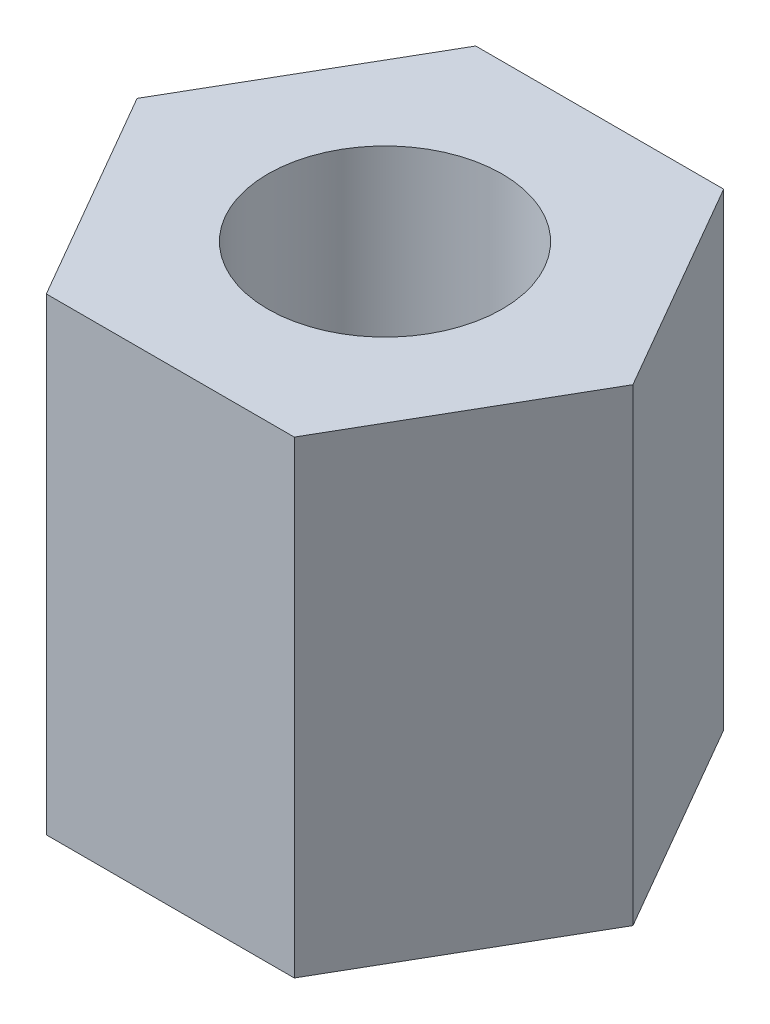
SolidWorks part; units mm, degrees
ref_plane "Front Plane" through (0, 0, 0) normal (0, 0, 1) x (1, 0, 0)
ref_plane "Top Plane" through (0, 0, 0) normal (0, 1, 0) x (1, 0, 0)
ref_plane "Right Plane" through (0, 0, 0) normal (1, 0, 0) x (0, 0, -1)
sketch "Sketch1" plane through (0, 0, 0) normal (0, 1, 0) x (1, 0, 0)
  line L1 (1.5877, 2.75) -> (-1.5877, 2.75)
  line L2 (-1.5877, 2.75) -> (-3.1754, 0)
  line L3 (-3.1754, 0) -> (-1.5877, -2.75)
  line L4 (-1.5877, -2.75) -> (1.5877, -2.75)
  line L5 (1.5877, -2.75) -> (3.1754, 0)
  line L6 (3.1754, 0) -> (1.5877, 2.75)
  circle A0 centre (0, 0) radius 1.5
  circle A1 centre (0, 0) radius 2.75 construction
  point P2 (0, 0)
  dimension "D1" = 5.5
  dimension "D2" = 3
extrude "Boss-Extrude1" add sketch "Sketch1" along normal blind 6
